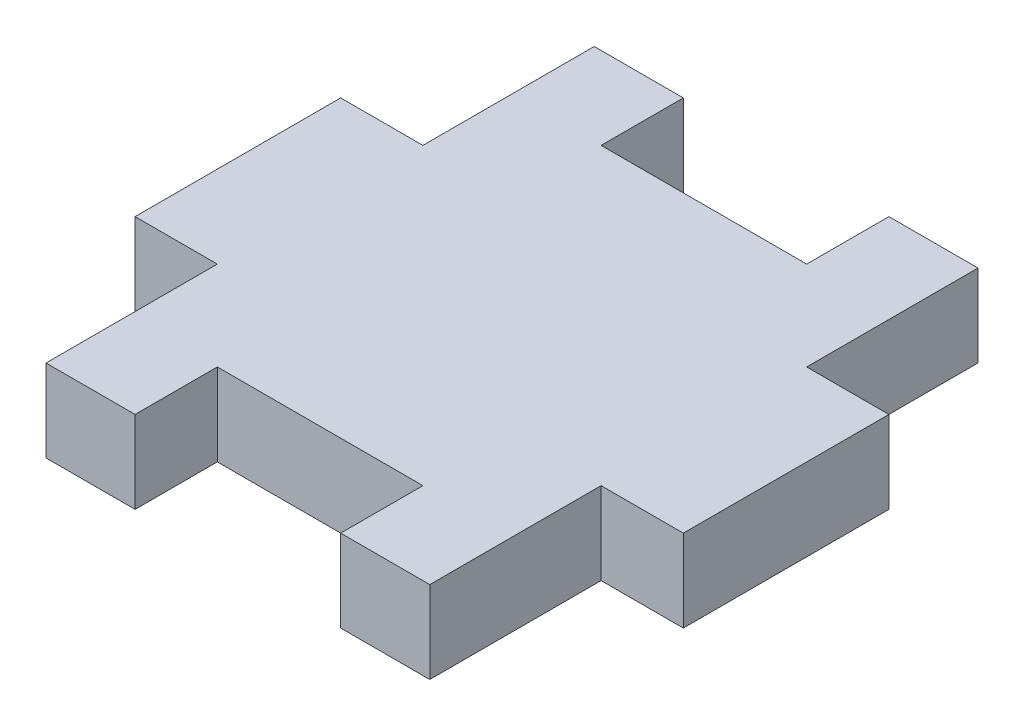
SolidWorks part; units mm, degrees
ref_plane "Alzado" through (0, 0, 0) normal (0, 0, 1) x (1, 0, 0)
ref_plane "Planta" through (0, 0, 0) normal (0, 1, 0) x (1, 0, 0)
ref_plane "Vista lateral" through (0, 0, 0) normal (1, 0, 0) x (0, 0, -1)
sketch "Croquis1" plane through (0, 0, 0) normal (0, 1, 0) x (1, 0, 0)
  line L0 (40, 27.5) -> (34, 27.5)
  line L1 (0, 0) -> (40, 0)
  line L2 (0, 0) -> (0, 40)
  line L3 (0, 40) -> (40, 40)
  line L4 (40, 0) -> (40, 40)
  line L5 (12.5, 40) -> (27.5, 40)
  line L6 (0, 40) -> (6, 40)
  line L7 (0, 40) -> (0, 27.5)
  line L8 (20, 40) -> (20, 0) construction
  line L9 (0, 20) -> (40, 20) construction
  line L10 (12.5, 40) -> (12.5, 34)
  line L11 (12.5, 34) -> (27.5, 34)
  line L12 (27.5, 40) -> (27.5, 34)
  line L13 (0, 27.5) -> (6, 27.5)
  line L14 (6, 40) -> (6, 27.5)
  line L15 (34, 40) -> (34, 27.5)
  line L16 (40, 40) -> (34, 40)
  line L17 (40, 40) -> (40, 27.5)
  line L18 (40, 0) -> (34, 0)
  line L19 (34, 0) -> (34, 12.5)
  line L20 (40, 12.5) -> (34, 12.5)
  line L21 (40, 0) -> (40, 12.5)
  line L22 (0, 12.5) -> (6, 12.5)
  line L23 (6, 0) -> (6, 12.5)
  line L24 (0, 0) -> (6, 0)
  line L25 (0, 0) -> (0, 12.5)
  line L26 (12.5, 6) -> (27.5, 6)
  line L27 (27.5, 0) -> (27.5, 6)
  line L28 (12.5, 0) -> (27.5, 0)
  line L29 (12.5, 0) -> (12.5, 6)
  point P5 (20, 34)
  dimension "D5" = 15
  dimension "D1" = 40
  dimension "D2" = 40
  dimension "D3" = 6
  dimension "D4" = 12.5
extrude "Saliente-Extruir1" add sketch "Croquis1" along normal blind 6
